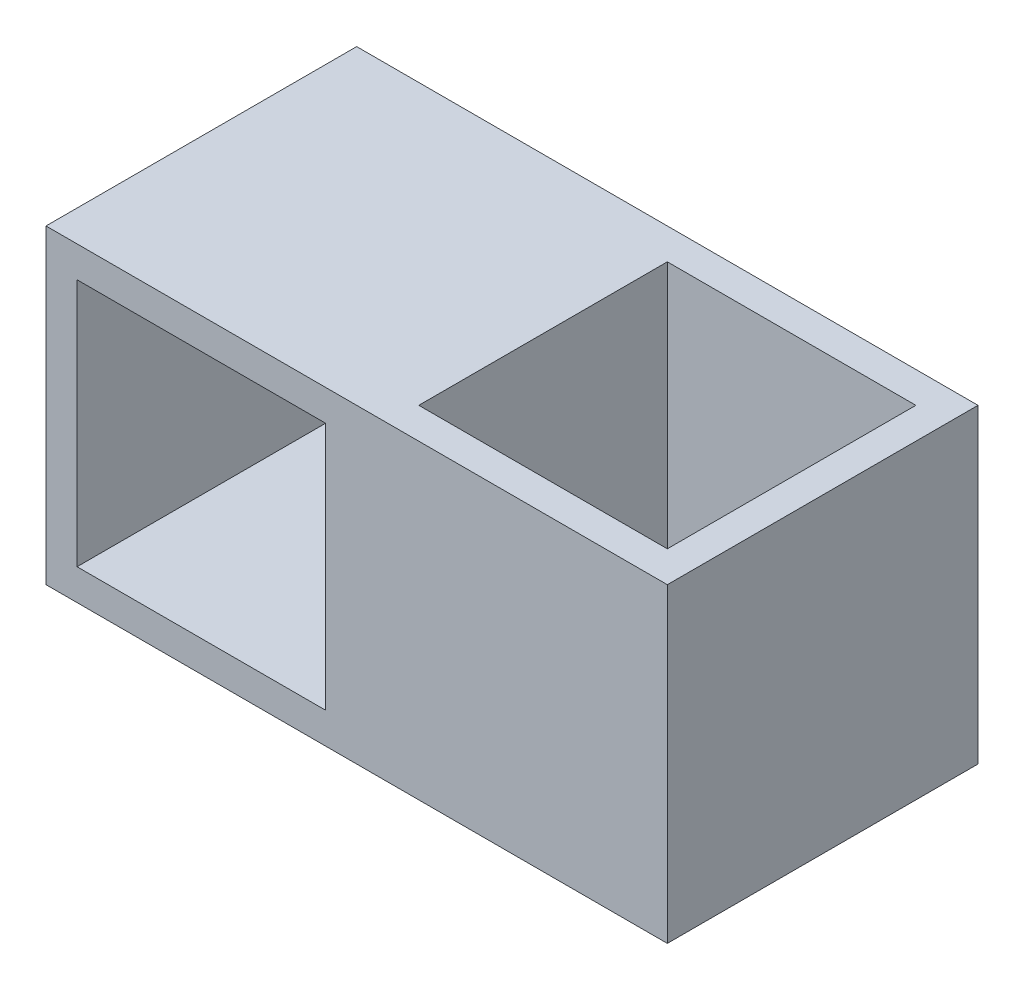
SolidWorks part; units mm, degrees
ref_plane "Front Plane" through (0, 0, 0) normal (0, 0, 1) x (1, 0, 0)
ref_plane "Top Plane" through (0, 0, 0) normal (0, 1, 0) x (1, 0, 0)
ref_plane "Right Plane" through (0, 0, 0) normal (1, 0, 0) x (0, 0, -1)
sketch "Sketch1" plane through (0, 0, 0) normal (0, 0, 1) x (1, 0, 0)
  line L5 (50, -25) -> (-50, -25)
  line L6 (50, -25) -> (50, 25)
  line L7 (50, 25) -> (-50, 25)
  line L8 (-50, -25) -> (-50, 25)
  line L9 (50, -25) -> (-50, 25) construction
  line L10 (50, 25) -> (-50, -25) construction
  point P0 (0, 0)
  dimension "D1" = 100
  dimension "D2" = 50
extrude "Boss-Extrude1" add sketch "Sketch1" along normal blind 50
sketch "Sketch2" plane through (0, -25, 0) normal (0, -1, 0) x (1, 0, 0)
  line L0 (-50, 25) -> (50, 25) construction
  line L1 (-50, 50) -> (-50, 0) construction
  line L2 (50, 50) -> (50, 0) construction
  line L4 (45, 5) -> (5, 5)
  line L5 (45, 5) -> (45, 45)
  line L6 (45, 45) -> (5, 45)
  line L7 (5, 5) -> (5, 45)
  line L8 (45, 5) -> (5, 45) construction
  line L9 (45, 45) -> (5, 5) construction
  point P6 (25, 25)
  dimension "D1" = 40
  dimension "D2" = 5
  dimension "D3" = 40
extrude "Cut-Extrude1" cut sketch "Sketch2" against normal up to next
sketch "Sketch3" plane through (0, 0, 50) normal (0, 0, 1) x (1, 0, 0)
  line L0 (-50, 0) -> (50, 0) construction
  line L1 (-50, 25) -> (-50, -25) construction
  line L2 (50, -25) -> (50, 25) construction
  line L4 (-5, 20) -> (-45, 20)
  line L5 (-5, 20) -> (-5, -20)
  line L6 (-5, -20) -> (-45, -20)
  line L7 (-45, 20) -> (-45, -20)
  line L8 (-5, 20) -> (-45, -20) construction
  line L9 (-5, -20) -> (-45, 20) construction
  point P6 (-25, 0)
  dimension "D1" = 40
  dimension "D2" = 40
  dimension "D3" = 5
extrude "Cut-Extrude2" cut sketch "Sketch3" against normal up to next
